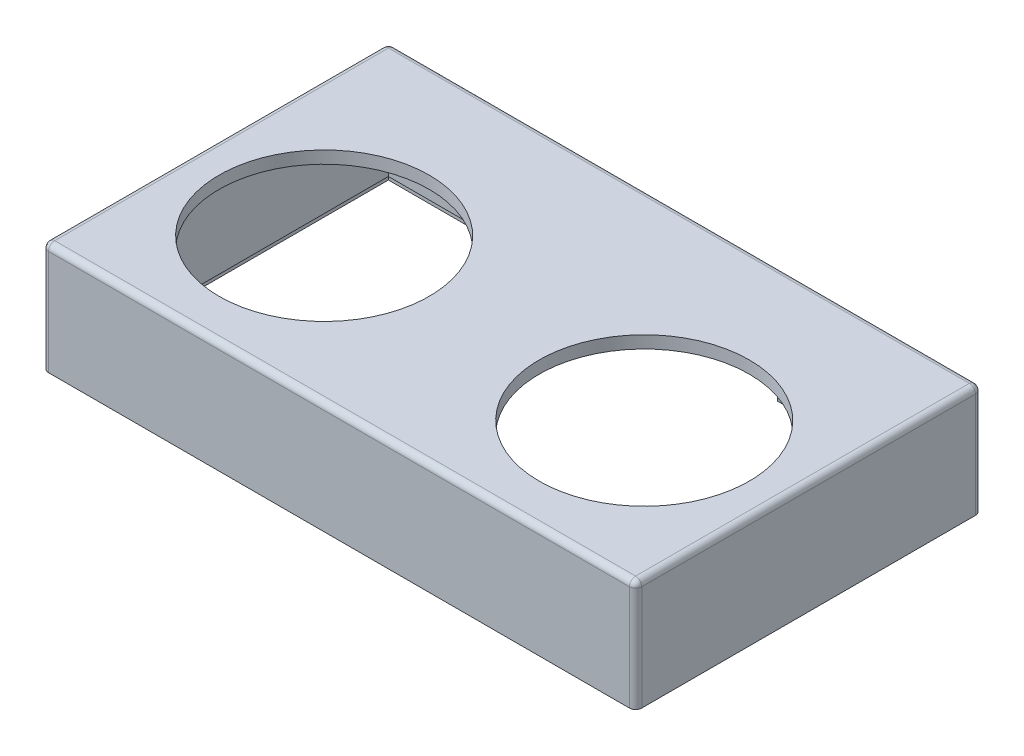
SolidWorks part; units mm, degrees
ref_plane "Front Plane" through (0, 0, 0) normal (0, 0, 1) x (1, 0, 0)
ref_plane "Top Plane" through (0, 0, 0) normal (0, 1, 0) x (1, 0, 0)
ref_plane "Right Plane" through (0, 0, 0) normal (1, 0, 0) x (0, 0, -1)
sketch "Sketch1" plane through (0, 0, 0) normal (0, 1, 0) x (1, 0, 0)
  line L1 (-24, -14) -> (24, -14)
  line L2 (-24, -14) -> (-24, 14)
  line L3 (-24, 14) -> (24, 14)
  line L4 (24, -14) -> (24, 14)
  line L5 (-24, -14) -> (24, 14) construction
  line L6 (-24, 14) -> (24, -14) construction
  point P0 (0, 0)
  dimension "D1" = 28
  dimension "D2" = 48
extrude "Boss-Extrude1" add sketch "Sketch1" along normal blind 9
sketch "Sketch2" plane through (0, 0, 0) normal (0, -1, 0) x (1, 0, 0)
  line L1 (-22.5, -12.5) -> (22.5, -12.5)
  line L2 (-22.5, -12.5) -> (-22.5, 12.5)
  line L3 (-22.5, 12.5) -> (22.5, 12.5)
  line L4 (22.5, -12.5) -> (22.5, 12.5)
  line L5 (-22.5, -12.5) -> (22.5, 12.5) construction
  line L6 (-22.5, 12.5) -> (22.5, -12.5) construction
  point P0 (0, 0)
  dimension "D1" = 45
  dimension "D2" = 25
extrude "Cut-Extrude1" cut sketch "Sketch2" against normal blind 8
sketch "Sketch3" plane through (0, 9, 0) normal (0, 1, 0) x (1, 0, 0)
  line L0 (-24, -14) -> (24, -14) construction
  line L1 (24, -14) -> (24, 14) construction
  circle A0 centre (-12.95, -2.25) radius 8.5
  circle A1 centre (12.95, -2.25) radius 8.5
  dimension "D1" = 17
  dimension "D2" = 17
  dimension "D3" = 25.9
  dimension "D4" = 11.75
  dimension "D5" = 11.05
  dimension "D6" = 11.75
extrude "Cut-Extrude2" cut sketch "Sketch3" against normal blind 22
sketch "Sketch4" plane through (0, 0, 0) normal (0, -1, 0) x (1, 0, 0)
  line L1 (-23.25, -13.25) -> (23.25, -13.25)
  line L2 (-23.25, -13.25) -> (-23.25, 13.25)
  line L3 (-23.25, 13.25) -> (23.25, 13.25)
  line L4 (23.25, -13.25) -> (23.25, 13.25)
  line L5 (-23.25, -13.25) -> (23.25, 13.25) construction
  line L6 (-23.25, 13.25) -> (23.25, -13.25) construction
  point P0 (0, 0)
  dimension "D1" = 46.5
  dimension "D2" = 26.5
extrude "Cut-Extrude3" cut sketch "Sketch4" against normal blind 1
sketch "Sketch10" plane through (0, 0, 0) normal (0, 0, 1) x (1, 0, 0)
  line L1 (9, 0) -> (1, 0)
  line L2 (9, 0) -> (9, 3.5)
  line L3 (9, 3.5) -> (1, 3.5)
  line L4 (1, 0) -> (1, 3.5)
  line L5 (9, 0) -> (1, 3.5) construction
  line L6 (9, 3.5) -> (1, 0) construction
  line L7 (22.5, 8) -> (22.5, 1) construction
  point P0 (5, 1.75)
  dimension "D1" = 8
  dimension "D2" = 3.5
  dimension "D3" = 1.75
  dimension "D4" = 13.5
extrude "Cut-Extrude4" cut sketch "Sketch10" against normal through all
fillet "Fillet5" radius 0.5 8 edges at (0, 9, -14) (24, 4.5, -14) (24, 4.5, 14) (-24, 4.5, -14) (-24, 9, 0) (-24, 4.5, 14) (0, 9, 14) (24, 9, 0)
